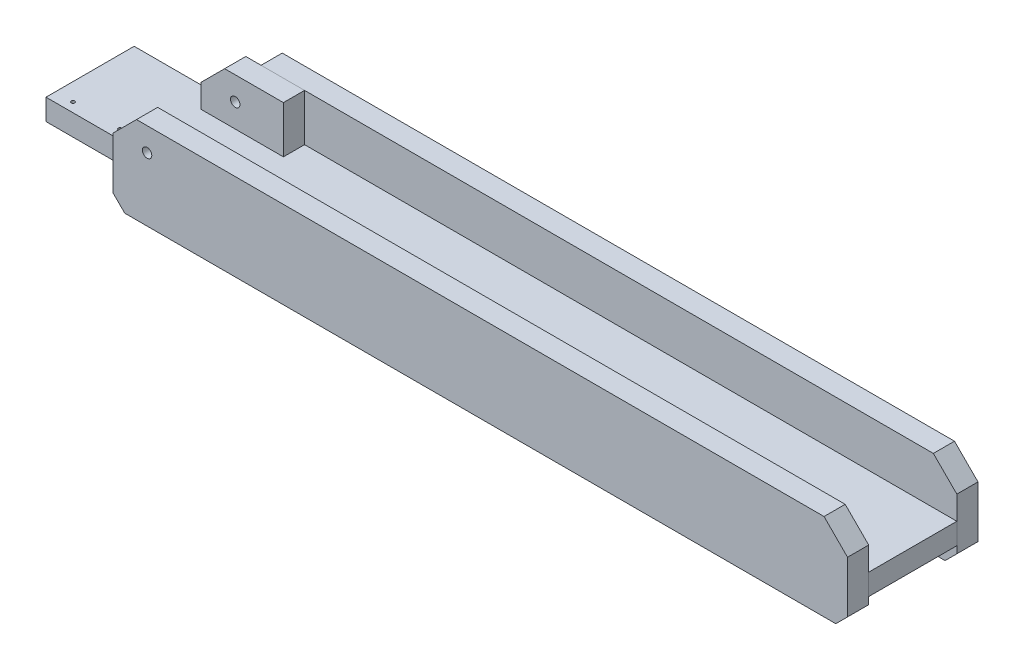
SolidWorks part; units mm, degrees
material "Pine"
ref_plane "Front Plane" through (0, 0, 0) normal (0, 0, 1) x (1, 0, 0)
ref_plane "Top Plane" through (0, 0, 0) normal (0, 1, 0) x (1, 0, 0)
ref_plane "Right Plane" through (0, 0, 0) normal (1, 0, 0) x (0, 0, -1)
sketch "Sketch1" plane through (0, 0, 0) normal (0, 1, 0) x (1, 0, 0)
  line L0 (0, -55) -> (0, 55) construction
  line L1 (0, 37.5) -> (700, 37.5)
  line L2 (0, 37.5) -> (0, -37.5)
  line L3 (0, -37.5) -> (700, -37.5)
  line L4 (700, 37.5) -> (700, -37.5)
  line L5 (-55, 0) -> (55, 0) construction
  dimension "D1" = 75
  dimension "D2" = 37.5
  dimension "D3" = 700
extrude "Boss-Extrude1" add sketch "Sketch1" along normal blind 18
ref_plane "Plane1" through (0, 0, 17) normal (0, 0, 1) x (1, 0, 0)
sketch "Sketch2" plane through (0, 0, 37.5) normal (0, 0, 1) x (1, 0, 0)
  line L1 (700, 18) -> (700, 0) construction
  line L2 (0, 18) -> (700, 18) construction
  line L3 (700, 58) -> (75, 58)
  line L4 (700, 58) -> (700, -16)
  line L5 (700, -16) -> (75, -16)
  line L7 (100, 95.2191) -> (100, -32.3771) construction
  line L8 (0, -40.7) -> (0, 40.7) construction
  line L9 (75, 58) -> (75, -16)
  line L10 (61.05, 0) -> (-61.05, 0) construction
  circle A2 centre (104, 38) radius 4
  dimension "D1" = 16
  dimension "D8" = 8
  dimension "D9" = 20
  dimension "D2" = 40
  dimension "D3" = 25
  dimension "D7" = 100
extrude "Boss-Extrude2" add sketch "Sketch2" along normal blind 18 separate body
chamfer "Chamfer1" distance 20 angle 45 2 edges at (700, 58, 46.5) (75, 58, 46.5)
chamfer "Chamfer2" distance 10 angle 45 2 edges at (700, -16, 46.5) (75, -16, 46.5)
mirror "Mirror1" about plane through (0, 0, 0) normal (0, 0, 1) of bodies 103
sketch "Sketch3" plane through (0, 0, -37.5) normal (0, 0, 1) x (1, 0, 0)
  line L0 (700, 18) -> (0, 18) construction
  line L1 (57.5772, 18) -> (145, 18)
  line L2 (145, 18) -> (145, 58)
  line L3 (700, -6) -> (700, 38) construction
  line L8 (700, -6) -> (700, 38)
  line L9 (700, 38) -> (680, 58)
  line L10 (680, 58) -> (95, 58)
  line L11 (95, 58) -> (75, 38)
  line L12 (75, 38) -> (75, -6)
  line L13 (75, -6) -> (85, -16)
  line L14 (85, -16) -> (690, -16)
  line L15 (690, -16) -> (700, -6)
  line L18 (145, 58) -> (95, 58)
  line L19 (95, 58) -> (75, 38)
  line L20 (75, 38) -> (75, 18)
  circle A0 centre (104, 38) radius 4 construction
  circle A1 centre (104, 38) radius 4
  line M11 (680, 58) -> (95, 58)
  line M12 (95, 58) -> (75, 38)
  line M13 (75, 38) -> (75, -6)
  circle M17 centre (104, 38) radius 4
  dimension "D2" = 555
  dimension "D1" = 0
extrude "Boss-Extrude3" add sketch "Sketch3" along normal blind 18 separate body contours L1 L2 M11 M12 M13 M17
sketch "Sketch4" plane through (75, 0, 0) normal (-1, 0, 0) x (0, 0, 1)
  line L0 (-37.5, 58) -> (-55.5, 58) construction
  line L1 (-37.5, 58) -> (-55.5, 58)
  line L2 (-55.5, -16) -> (-37.5, -16) construction
  line L3 (-55.5, -16) -> (-37.5, -16)
  line L4 (-55.5, 58) -> (-55.5, -16)
  line L6 (-37.5, -16) -> (-37.5, 58)
extrude "Cut-Extrude1" cut sketch "Sketch4" against normal blind 33
sketch "Sketch5" plane through (108, 0, 0) normal (-1, 0, 0) x (0, 0, 1)
  circle A0 centre (-45.5, -1) radius 1.5 construction
  circle A1 centre (-45.5, -1) radius 1.5
  circle A2 centre (-45.5, 39) radius 1.5 construction
  circle A3 centre (-45.5, 39) radius 1.5
extrude "Cut-Extrude2" cut sketch "Sketch5" against normal blind 10
sketch "Sketch6" plane through (0, 18, 0) normal (0, 1, 0) x (1, 0, 0)
  circle A0 centre (55, -29.5) radius 1.5 construction
  circle A1 centre (15, -29.5) radius 1.5 construction
  circle A2 centre (55, -29.5) radius 1.5
  circle A3 centre (15, -29.5) radius 1.5
extrude "Cut-Extrude3" cut sketch "Sketch6" against normal blind 10
